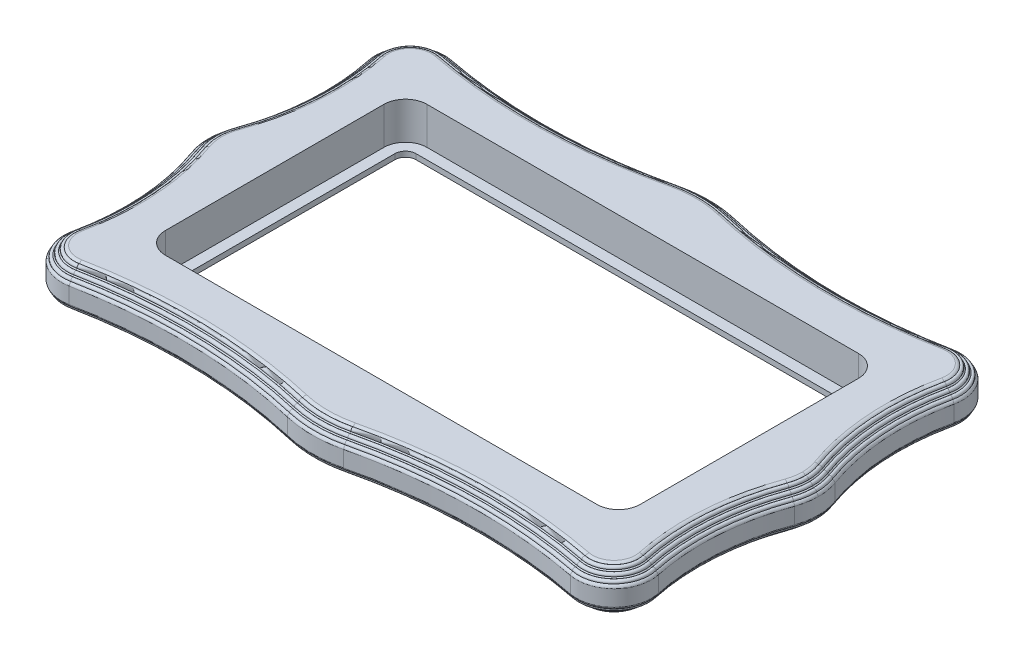
SolidWorks part; units mm, degrees
ref_plane "Front Plane" through (0, 0, 0) normal (0, 0, 1) x (1, 0, 0)
ref_plane "Top Plane" through (0, 0, 0) normal (0, 1, 0) x (1, 0, 0)
ref_plane "Right Plane" through (0, 0, 0) normal (1, 0, 0) x (0, 0, -1)
sketch "Sketch1" plane through (0, 0, 0) normal (0, 1, 0) x (1, 0, 0)
  line L0 (0, 22.5) -> (0, 30.5) construction
  line L1 (50.5, -30.5) -> (-50.5, -30.5) construction
  line L2 (50.5, -30.5) -> (50.5, 30.5) construction
  line L3 (50.5, 30.5) -> (-50.5, 30.5) construction
  line L4 (-50.5, -30.5) -> (-50.5, 30.5) construction
  line L5 (50.5, -30.5) -> (-50.5, 30.5) construction
  line L6 (50.5, 30.5) -> (-50.5, -30.5) construction
  line L7 (-42.5, 22.5) -> (42.5, 22.5) construction
  line L8 (-42.5, 22.5) -> (-42.5, -22.5) construction
  line L9 (-42.5, -22.5) -> (42.5, -22.5) construction
  line L10 (42.5, 22.5) -> (42.5, -22.5) construction
  line L11 (-42.5, 22.5) -> (42.5, -22.5) construction
  line L12 (-42.5, -22.5) -> (42.5, 22.5) construction
  line L13 (42.5, 0) -> (50.5, 0) construction
  line L14 (57.5, 0) -> (50.5, 0) construction
  line L19 (-46.5, 26.5) -> (46.5, 26.5) construction
  line L20 (-46.5, 26.5) -> (-46.5, -26.5) construction
  line L21 (-46.5, -26.5) -> (46.5, -26.5) construction
  line L22 (46.5, 26.5) -> (46.5, -26.5) construction
  line L23 (-46.5, 26.5) -> (46.5, -26.5) construction
  line L24 (-46.5, -26.5) -> (46.5, 26.5) construction
  line L25 (-57.5, 37.5) -> (57.5, 37.5)
  line L26 (-57.5, 37.5) -> (-57.5, -37.5)
  line L27 (-57.5, -37.5) -> (57.5, -37.5)
  line L28 (57.5, 37.5) -> (57.5, -37.5)
  line L29 (-57.5, 37.5) -> (57.5, -37.5) construction
  line L30 (-57.5, -37.5) -> (57.5, 37.5) construction
  line L31 (0, 30.5) -> (0, 37.5) construction
  circle A0 centre (46.5, 26.5) radius 3.625 construction
  circle A1 centre (-46.5, 26.5) radius 3.625 construction
  circle A2 centre (46.5, -26.5) radius 3.625 construction
  circle A3 centre (-46.5, -26.5) radius 3.625 construction
  point P0 (0, 0)
  point P6 (0, 0)
  point P17 (0, 0)
  point P24 (0, 0)
  point P29 (46.5, 0)
  point P30 (0, 26.5)
  dimension "D5" = 7.25
  dimension "D1" = 85
  dimension "D2" = 45
  dimension "D3" = 8
  dimension "D4" = 7
extrude "Base" add sketch "Sketch1" along normal blind 8
sketch "Path" plane through (0, 8, 0) normal (0, 1, 0) x (1, 0, 0)
  line L0 (51.25, 0) -> (50.5, 0) construction
  line L1 (28.0361, 31.25) -> (28.0361, 30.5) construction
  line L2 (-4.5909, 34.5) -> (4.5909, 34.5) construction
  line L3 (-54.5, 4.5909) -> (-54.5, -4.5909) construction
  line L4 (-50.5, -30.5) -> (-50.5, 30.5) construction
  line L5 (-50.5, 30.5) -> (50.5, 30.5) construction
  line L6 (-57.5, 37.5) -> (-57.5, -37.5) construction
  line L7 (57.5, 37.5) -> (-57.5, 37.5) construction
  line L8 (0, 34.5) -> (0, 37.5) construction
  line L9 (-54.5, 0) -> (-57.5, 0) construction
  line L10 (0, 0) -> (-50.5, 30.5) construction
  line L11 (-51.25, 31.25) -> (-51.25, -31.25) construction
  line L12 (-51.25, 31.25) -> (51.25, 31.25) construction
  line L13 (-50.5, 0) -> (-41.3182, 0) construction
  line L14 (-41.3182, 0) -> (-32.1364, 0) construction
  line L15 (-32.1364, 0) -> (-22.9545, 0) construction
  line L16 (-22.9545, 0) -> (-13.7727, 0) construction
  line L17 (-13.7727, 0) -> (-4.5909, 0) construction
  line L18 (-4.5909, 0) -> (4.5909, 0) construction
  line L19 (-4.5909, 33.9678) -> (4.5909, 33.9678) construction
  line L20 (-28.0361, 30.5) -> (-28.0361, 24.9545) construction
  line L21 (-28.0361, 24.9545) -> (-28.0361, 19.4091) construction
  line L22 (-28.0361, 19.4091) -> (-28.0361, 13.8636) construction
  line L23 (-28.0361, 13.8636) -> (-28.0361, 8.3182) construction
  line L24 (-28.0361, 8.3182) -> (-28.0361, 2.7727) construction
  line L25 (-28.0361, 2.7727) -> (-28.0361, -2.7727) construction
  line L26 (-54.0165, 2.7727) -> (-54.0165, -2.7727) construction
  line L27 (0, 37.5) -> (0, 46.6818) construction
  line L28 (-57.5, 0) -> (-66.6818, 0) construction
  line L29 (-28.0361, 31.25) -> (-28.0361, 30.5) construction
  line L30 (-51.25, 0) -> (-50.5, 0) construction
  line L31 (54.0165, 2.7727) -> (54.0165, -2.7727) construction
  line L32 (28.0361, 2.7727) -> (28.0361, -2.7727) construction
  line L33 (28.0361, 8.3182) -> (28.0361, 2.7727) construction
  line L34 (28.0361, 13.8636) -> (28.0361, 8.3182) construction
  line L35 (28.0361, 19.4091) -> (28.0361, 13.8636) construction
  line L36 (28.0361, 24.9545) -> (28.0361, 19.4091) construction
  line L37 (28.0361, 30.5) -> (28.0361, 24.9545) construction
  line L38 (13.7727, 0) -> (4.5909, 0) construction
  line L39 (22.9545, 0) -> (13.7727, 0) construction
  line L40 (32.1364, 0) -> (22.9545, 0) construction
  line L41 (41.3182, 0) -> (32.1364, 0) construction
  line L42 (50.5, 0) -> (41.3182, 0) construction
  line L43 (51.25, 31.25) -> (51.25, -31.25) construction
  line L44 (0, 0) -> (50.5, 30.5) construction
  line L45 (54.5, 0) -> (57.5, 0) construction
  line L46 (50.5, -30.5) -> (50.5, 30.5) construction
  line L47 (54.5, 4.5909) -> (54.5, -4.5909) construction
  line L48 (0, 0) -> (50.5, -30.5) construction
  line L49 (50.5, 0) -> (41.3182, 0) construction
  line L50 (41.3182, 0) -> (32.1364, 0) construction
  line L51 (32.1364, 0) -> (22.9545, 0) construction
  line L52 (22.9545, 0) -> (13.7727, 0) construction
  line L53 (13.7727, 0) -> (4.5909, 0) construction
  line L54 (28.0361, -30.5) -> (28.0361, -24.9545) construction
  line L55 (28.0361, -24.9545) -> (28.0361, -19.4091) construction
  line L56 (28.0361, -19.4091) -> (28.0361, -13.8636) construction
  line L57 (28.0361, -13.8636) -> (28.0361, -8.3182) construction
  line L58 (28.0361, -8.3182) -> (28.0361, -2.7727) construction
  line L59 (-51.25, 0) -> (-50.5, 0) construction
  line L60 (-28.0361, -31.25) -> (-28.0361, -30.5) construction
  line L61 (0, -37.5) -> (0, -46.6818) construction
  line L62 (-28.0361, -8.3182) -> (-28.0361, -2.7727) construction
  line L63 (-28.0361, -13.8636) -> (-28.0361, -8.3182) construction
  line L64 (-28.0361, -19.4091) -> (-28.0361, -13.8636) construction
  line L65 (-28.0361, -24.9545) -> (-28.0361, -19.4091) construction
  line L66 (-28.0361, -30.5) -> (-28.0361, -24.9545) construction
  line L67 (-4.5909, -33.9678) -> (4.5909, -33.9678) construction
  line L68 (-4.5909, 0) -> (4.5909, 0) construction
  line L69 (-13.7727, 0) -> (-4.5909, 0) construction
  line L70 (-22.9545, 0) -> (-13.7727, 0) construction
  line L71 (-32.1364, 0) -> (-22.9545, 0) construction
  line L72 (-41.3182, 0) -> (-32.1364, 0) construction
  line L73 (-50.5, 0) -> (-41.3182, 0) construction
  line L74 (-51.25, -31.25) -> (51.25, -31.25) construction
  line L75 (0, 0) -> (-50.5, -30.5) construction
  line L76 (0, -34.5) -> (0, -37.5) construction
  line L77 (-50.5, -30.5) -> (50.5, -30.5) construction
  line L78 (-4.5909, -34.5) -> (4.5909, -34.5) construction
  line L79 (28.0361, -31.25) -> (28.0361, -30.5) construction
  line L80 (51.25, 0) -> (50.5, 0) construction
  arc A0 (4.5909, 33.9678) -> (-4.5909, 33.9678) centre (0, 14.4322) ccw
  arc A1 (-54.0165, -2.7727) -> (-54.0165, 2.7727) centre (-46.3077, 0) cw
  circle A2 centre (-48.36, 29.2075) radius 4 construction
  arc A3 (-54.0165, 2.7727) -> (-52.2727, 28.3765) centre (-98.1256, 18.6381) ccw
  arc A4 (-4.5909, 33.9678) -> (-47.5966, 33.134) centre (-28.0361, 133.734) cw
  arc A5 (-52.2727, 28.3765) -> (-47.5966, 33.134) centre (-48.36, 29.2075) cw
  circle A6 centre (48.36, 29.2075) radius 4 construction
  arc A7 (52.2727, 28.3765) -> (47.5966, 33.134) centre (48.36, 29.2075) ccw
  arc A8 (4.5909, 33.9678) -> (47.5966, 33.134) centre (28.0361, 133.734) ccw
  arc A9 (54.0165, 2.7727) -> (52.2727, 28.3765) centre (98.1256, 18.6381) cw
  arc A10 (54.0165, -2.7727) -> (54.0165, 2.7727) centre (46.3077, 0) ccw
  circle A11 centre (48.36, -29.2075) radius 4 construction
  circle A12 centre (-48.36, -29.2075) radius 4 construction
  arc A13 (54.0165, -2.7727) -> (52.2727, -28.3765) centre (98.1256, -18.6381) ccw
  arc A14 (4.5909, -33.9678) -> (47.5966, -33.134) centre (28.0361, -133.734) cw
  arc A15 (52.2727, -28.3765) -> (47.5966, -33.134) centre (48.36, -29.2075) cw
  arc A16 (-52.2727, -28.3765) -> (-47.5966, -33.134) centre (-48.36, -29.2075) ccw
  arc A17 (-4.5909, -33.9678) -> (-47.5966, -33.134) centre (-28.0361, -133.734) ccw
  arc A18 (-54.0165, -2.7727) -> (-52.2727, -28.3765) centre (-98.1256, -18.6381) cw
  arc A19 (4.5909, -33.9678) -> (-4.5909, -33.9678) centre (0, -14.4322) cw
  point P37 (-50.5, 0)
  point P72 (0, 33.9678)
  point P73 (0, 0)
  point P78 (0, 31.25)
  point P82 (0, 30.5)
  point P96 (50.5, 0)
  point P97 (51.25, 0)
  point P109 (28.0361, 0)
  point P110 (54.0165, 0)
  point P117 (-54.0165, 0)
  point P118 (-28.0361, 0)
  point P130 (-51.25, 0)
  point P132 (-50.5, 0)
  point P146 (0, -30.5)
  point P147 (0, -31.25)
  point P148 (0, 0)
  point P149 (0, -33.9678)
  dimension "D5" = 8
  dimension "D1" = 7
  dimension "D2" = 7
  dimension "D3" = 3
  dimension "D4" = 2.5
  dimension "D7" = 0.75
sketch "Profile" plane through (0, 0, 0) normal (0, 0, 1) x (1, 0, 0)
  line L0 (54.5, 8) -> (57.5, 8)
  line L1 (57.5, 8) -> (57.5, 5.5) construction
  line L2 (57.5, 8) -> (55.25, 7.375) construction
  line L3 (57.5, 8) -> (56, 6.75) construction
  line L4 (57.5, 8) -> (56.75, 6.125) construction
  line L5 (55.25, 7.375) -> (54.5, 8) construction
  line L6 (55.25, 7.375) -> (56, 6.75) construction
  line L7 (56, 6.75) -> (56.75, 6.125) construction
  line L8 (56.75, 6.125) -> (57.5, 5.5) construction
  line L9 (56, 6.75) -> (57.5, 6.75) construction
  line L10 (56.75, 6.125) -> (57.5, 6.125) construction
  line L11 (55.25, 7.375) -> (57.5, 7.375) construction
  line L12 (57.5, 8) -> (67.5, 8)
  line L13 (67.5, 8) -> (67.5, 5.5)
  line L15 (57.5, 5.5) -> (57.5, 2.5)
  line L16 (57.5, 4) -> (67.5, 4) construction
  line L17 (57.5, 5.5) -> (67.5, 5.5) construction
  line L18 (67.5, 2.5) -> (67.5, 5.5)
  line L19 (67.5, 4) -> (70.5, 4) construction
  line L20 (57.5, 2.5) -> (67.5, 2.5) construction
  line L21 (55.25, 0.625) -> (57.5, 0.625) construction
  line L22 (56.75, 1.875) -> (57.5, 1.875) construction
  line L23 (56, 1.25) -> (57.5, 1.25) construction
  line L24 (56.75, 1.875) -> (57.5, 2.5) construction
  line L25 (56, 1.25) -> (56.75, 1.875) construction
  line L26 (55.25, 0.625) -> (56, 1.25) construction
  line L27 (55.25, 0.625) -> (54.5, 0) construction
  line L28 (57.5, 0) -> (56.75, 1.875) construction
  line L29 (57.5, 0) -> (56, 1.25) construction
  line L30 (57.5, 0) -> (55.25, 0.625) construction
  line L31 (57.5, 0) -> (57.5, 2.5) construction
  line L32 (67.5, 0) -> (67.5, 2.5)
  line L33 (57.5, 0) -> (67.5, 0)
  line L34 (54.5, 0) -> (57.5, 0)
  line L37 (-57.5, 0) -> (57.5, 0) construction
  circle A0 centre (55.25, 7.375) radius 0.39 construction
  circle A1 centre (56, 6.75) radius 0.39 construction
  circle A2 centre (56.75, 6.125) radius 0.39 construction
  arc A3 (56.75, 6.125) -> (57.5, 5.5) centre (56.75, 5.3625) cw construction
  arc A4 (56, 6.75) -> (56.75, 6.125) centre (56, 5.9875) cw construction
  arc A5 (55.25, 7.375) -> (56, 6.75) centre (55.25, 6.6125) cw construction
  arc A6 (54.5, 8) -> (55.25, 7.375) centre (54.5, 7.2375) cw construction
  arc A7 (54.5, 8) -> (55.0839, 7.7279) centre (54.5, 7.2375) cw
  arc A8 (55.0839, 7.7279) -> (55.627, 7.2753) centre (55.25, 7.375) cw
  arc A9 (55.627, 7.2753) -> (55.8339, 7.1029) centre (55.25, 6.6125) cw
  arc A10 (55.8339, 7.1029) -> (56.377, 6.6503) centre (56, 6.75) cw
  arc A11 (56.377, 6.6503) -> (56.5839, 6.4779) centre (56, 5.9875) cw
  arc A12 (56.5839, 6.4779) -> (57.127, 6.0253) centre (56.75, 6.125) cw
  arc A13 (57.127, 6.0253) -> (57.5, 5.5) centre (56.75, 5.3625) cw
  arc A14 (54.5, 0) -> (55.25, 0.625) centre (54.5, 0.7625) ccw construction
  arc A15 (55.25, 0.625) -> (56, 1.25) centre (55.25, 1.3875) ccw construction
  arc A16 (56, 1.25) -> (56.75, 1.875) centre (56, 2.0125) ccw construction
  arc A17 (56.75, 1.875) -> (57.5, 2.5) centre (56.75, 2.6375) ccw construction
  circle A18 centre (56.75, 1.875) radius 0.39 construction
  circle A19 centre (56, 1.25) radius 0.39 construction
  circle A20 centre (55.25, 0.625) radius 0.39 construction
  arc A21 (57.127, 1.9747) -> (57.5, 2.5) centre (56.75, 2.6375) ccw
  arc A22 (56.5839, 1.5221) -> (57.127, 1.9747) centre (56.75, 1.875) ccw
  arc A23 (56.377, 1.3497) -> (56.5839, 1.5221) centre (56, 2.0125) ccw
  arc A24 (55.8339, 0.8971) -> (56.377, 1.3497) centre (56, 1.25) ccw
  arc A25 (55.627, 0.7247) -> (55.8339, 0.8971) centre (55.25, 1.3875) ccw
  arc A26 (55.0839, 0.2721) -> (55.627, 0.7247) centre (55.25, 0.625) ccw
  arc A27 (54.5, 0) -> (55.0839, 0.2721) centre (54.5, 0.7625) ccw
  dimension "D3" = 0.78
  dimension "D1" = 3
  dimension "D2" = 2.5
  dimension "D4" = 10
sweep "Sweep Cut" cut profiles "Profile" path "Path"
sketch "Sketch4" plane through (0, 0, 0) normal (0, 1, 0) x (1, 0, 0)
  circle A0 centre (-46.5, -26.5) radius 3.625 construction
  circle A1 centre (46.5, -26.5) radius 3.625 construction
  circle A2 centre (46.5, 26.5) radius 3.625 construction
  circle A3 centre (-46.5, 26.5) radius 3.625 construction
  circle A4 centre (-46.5, -26.5) radius 3.625
  circle A5 centre (46.5, -26.5) radius 3.625
  circle A6 centre (46.5, 26.5) radius 3.625
  circle A7 centre (-46.5, 26.5) radius 3.625
sketch "Sketch10" plane through (0, 8, 0) normal (0, 1, 0) x (1, 0, 0)
  line L1 (40.5, -22.5) -> (-40.5, -22.5)
  line L2 (42.5, -20.5) -> (42.5, 20.5)
  line L3 (40.5, 22.5) -> (-40.5, 22.5)
  line L4 (-42.5, -20.5) -> (-42.5, 20.5)
  line L5 (42.5, -22.5) -> (-42.5, 22.5) construction
  line L6 (42.5, 22.5) -> (-42.5, -22.5) construction
  arc A0 (-40.5, -22.5) -> (-42.5, -20.5) centre (-40.5, -20.5) cw
  arc A1 (40.5, -22.5) -> (42.5, -20.5) centre (40.5, -20.5) ccw
  arc A2 (42.5, 20.5) -> (40.5, 22.5) centre (40.5, 20.5) ccw
  arc A3 (-40.5, 22.5) -> (-42.5, 20.5) centre (-40.5, 20.5) ccw
  point P0 (0, 0)
  dimension "D1" = 2
  dimension "D2" = 85
  dimension "D3" = 45
extrude "Screen Size Cut" cut sketch "Sketch10" against normal up to surface (8 mm away) up to face at (3.1916, 0, 0)
sketch "Sketch12" plane through (0, 8, 0) normal (0, 1, 0) x (1, 0, 0)
  line L4 (-42.5, 20.5) -> (-42.5, -20.5)
  line L5 (-40.5, -22.5) -> (40.5, -22.5)
  line L6 (42.5, -20.5) -> (42.5, 20.5)
  line L7 (40.5, 22.5) -> (-40.5, 22.5)
  line L8 (-42.5, 20.5) -> (-42.5, -20.5) construction
  line L9 (-40.5, -22.5) -> (40.5, -22.5) construction
  line L10 (42.5, -20.5) -> (42.5, 20.5) construction
  line L11 (40.5, 22.5) -> (-40.5, 22.5) construction
  line L12 (44.5417, -20.5) -> (44.5417, 20.5)
  line L13 (40.5, 24.5417) -> (-40.5, 24.5417)
  line L14 (-44.5417, 20.5) -> (-44.5417, -20.5)
  line L15 (-40.5, -24.5417) -> (40.5, -24.5417)
  arc A4 (-42.5, -20.5) -> (-40.5, -22.5) centre (-40.5, -20.5) ccw
  arc A5 (40.5, -22.5) -> (42.5, -20.5) centre (40.5, -20.5) ccw
  arc A6 (42.5, 20.5) -> (40.5, 22.5) centre (40.5, 20.5) ccw
  arc A7 (-40.5, 22.5) -> (-42.5, 20.5) centre (-40.5, 20.5) ccw
  arc A8 (-42.5, -20.5) -> (-40.5, -22.5) centre (-40.5, -20.5) ccw construction
  arc A9 (40.5, -22.5) -> (42.5, -20.5) centre (40.5, -20.5) ccw construction
  arc A10 (42.5, 20.5) -> (40.5, 22.5) centre (40.5, 20.5) ccw construction
  arc A11 (-40.5, 22.5) -> (-42.5, 20.5) centre (-40.5, 20.5) ccw construction
  arc A12 (44.5417, 20.5) -> (40.5, 24.5417) centre (40.5, 20.5) ccw
  arc A13 (-40.5, 24.5417) -> (-44.5417, 20.5) centre (-40.5, 20.5) ccw
  arc A14 (-44.5417, -20.5) -> (-40.5, -24.5417) centre (-40.5, -20.5) ccw
  arc A15 (40.5, -24.5417) -> (44.5417, -20.5) centre (40.5, -20.5) ccw
  circle A16 centre (46.5, 26.5) radius 3.625 construction
  circle A17 centre (46.5, 26.5) radius 3.625 construction
  dimension "D1" = 0.8186
  dimension "D2" = 0
extrude "Device Shape Cut" cut sketch "Sketch12" against normal offset from surface (7 mm away) 1 up to face at (0, 0, 0)
extrude "Support Pole Hole Cut" cut sketch "Sketch4" along normal blind 3
equation "\"D1@Sketch1\"=\"screen height\""
equation "\"D2@Sketch1\"=\"screen width\""
equation "\"D5@Sketch1\"=\"support pole tight fit hole dia\""
equation "\"D2@Sketch10\"=\"screen height\""
equation "\"D3@Sketch10\"=\"screen width\""
equation "\"screen width\"= 45.00mm"
equation "\"screen height\"= 85.00mm"
equation "\"top cutoff\" = 2.00mm"
equation "\"A\" = \"screen width\" / 2"
equation "\"B\" = \"screen width\" / 2"
equation "\"screen hypotenuse\" = sqr ( ( \"A\" * \"A\" ) + ( \"B\" * \"B\" ) )"
equation "\"a2\" = \"top cutoff\" "
equation "\"b2\" = \"top cutoff\""
equation "\"top cutoff hypotenuse\" = sqr ( ( \"a2\" * \"a2\" ) + ( \"b2\" * \"b2\" ) )"
equation "\"total hypotenuse\" = \"screen hypotenuse\" - \"top cutoff hypotenuse\""
equation "\"image display width\" = ( \"A\" / 3 ) * 2"
equation "\"image display height\" = ( \"B\" / 3 ) * 2"
equation "\"support pole dia\" = 7.00mm"
equation "\"support pole loose fit hole dia\" = \"support pole dia\"+0.5"
equation "\"support pole tight fit hole dia\" = \"support pole dia\"+0.25"
